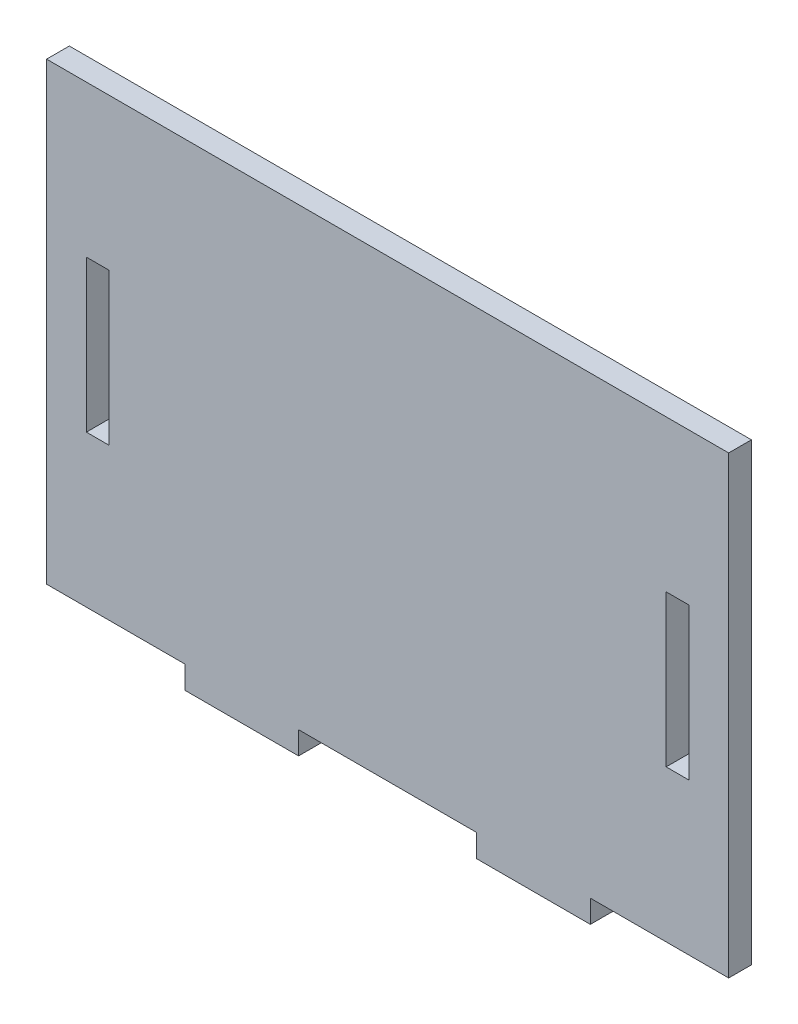
SolidWorks part; units mm, degrees
material "雪松树"
ref_plane "前视基准面" through (0, 0, 0) normal (0, 0, 1) x (1, 0, 0)
ref_plane "上视基准面" through (0, 0, 0) normal (0, 1, 0) x (1, 0, 0)
ref_plane "右视基准面" through (0, 0, 0) normal (1, 0, 0) x (0, 0, -1)
other "Configuration Table"
sketch "草图1" plane through (0, 0, 0) normal (0, 0, 1) x (1, 0, 0)
  line L0 (45, 52.4822) -> (45, -24.3184) construction
  line L1 (0, 0) -> (90, 0)
  line L2 (0, 0) -> (0, 60)
  line L3 (0, 60) -> (90, 60)
  line L4 (90, 0) -> (90, 60)
  line L5 (33.25, -3) -> (18.25, -3)
  line L6 (56.75, 0) -> (71.75, 0)
  line L7 (56.75, 0) -> (56.75, -3)
  line L8 (56.75, -3) -> (71.75, -3)
  line L9 (71.75, 0) -> (71.75, -3)
  line L10 (18.25, 0) -> (18.25, -3)
  line L11 (33.25, 0) -> (18.25, 0)
  line L12 (33.25, 0) -> (33.25, -3)
  line L13 (84.75, 20) -> (81.75, 20)
  line L14 (5.25, 40) -> (8.25, 40)
  line L15 (5.25, 40) -> (5.25, 20)
  line L16 (5.25, 20) -> (8.25, 20)
  line L17 (8.25, 40) -> (8.25, 20)
  line L18 (81.75, 40) -> (81.75, 20)
  line L19 (84.75, 40) -> (81.75, 40)
  line L20 (84.75, 40) -> (84.75, 20)
  dimension "D1" = 60
  dimension "D2" = 90
  dimension "D3" = 45
  dimension "D4" = 3
  dimension "D5" = 15
  dimension "D6" = 11.75
  dimension "D7" = 20
  dimension "D8" = 3
  dimension "D9" = 20
  dimension "D10" = 36.75
extrude "凸台-拉伸1" add sketch "草图1" along normal blind 3 contours L3 L0 L1 L4 L19 L20 L13 L18 | L0 L3 L2 L1 L14 L17 L16 L15 | L12 L1 L10 L5 | L9 L1 L7 L8
